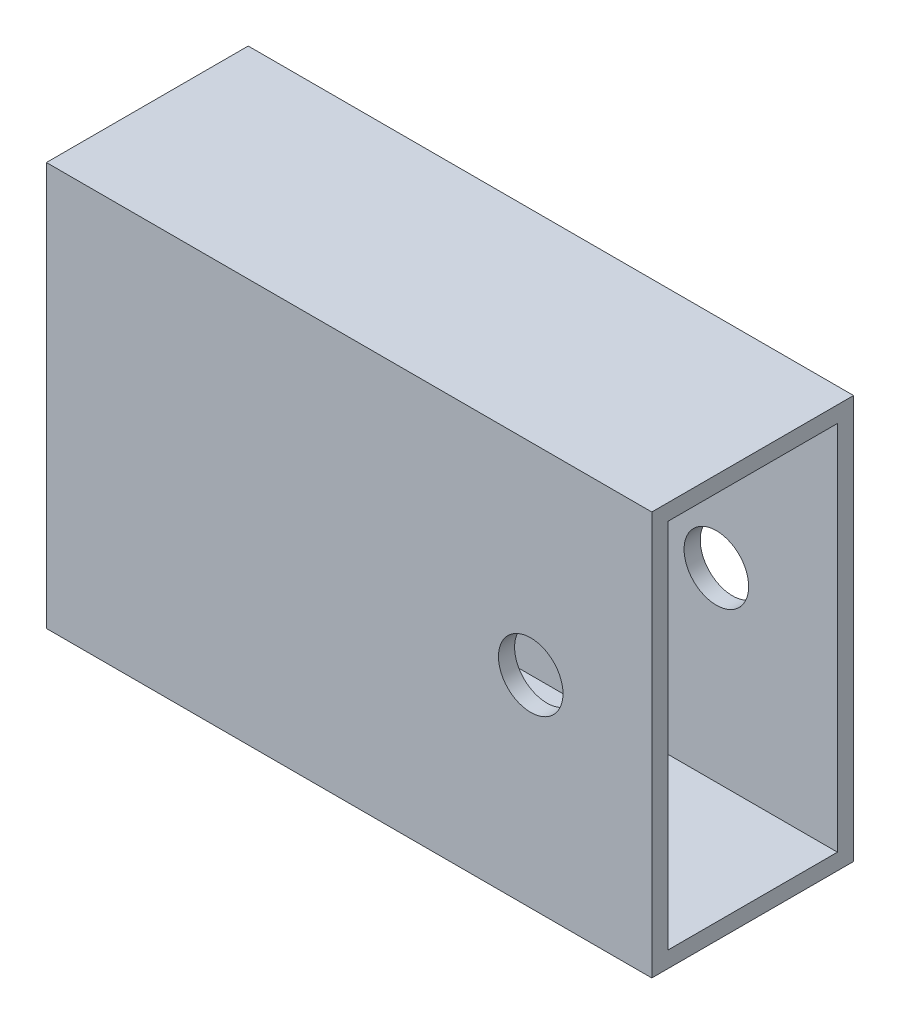
SolidWorks part; units mm, degrees
ref_plane "Front Plane" through (0, 0, 0) normal (0, 0, 1) x (1, 0, 0)
ref_plane "Top Plane" through (0, 0, 0) normal (0, 1, 0) x (1, 0, 0)
ref_plane "Right Plane" through (0, 0, 0) normal (1, 0, 0) x (0, 0, -1)
sketch "Sketch1" plane through (0, 0, 0) normal (1, 0, 0) x (0, 0, -1)
  line L1 (0, 0) -> (25, 0)
  line L2 (0, 0) -> (0, 50)
  line L3 (0, 50) -> (25, 50)
  line L4 (25, 0) -> (25, 50)
  line L5 (2, 2) -> (23, 2)
  line L6 (2, 2) -> (2, 48)
  line L7 (2, 48) -> (23, 48)
  line L8 (23, 2) -> (23, 48)
  dimension "D1" = 25
  dimension "D2" = 50
  dimension "D3" = 2
  dimension "D4" = 2
  dimension "D5" = 2
  dimension "D6" = 2
extrude "Boss-Extrude1" add sketch "Sketch1" along normal blind 75
sketch "Sketch2" plane through (0, 0, 0) normal (0, 0, 1) x (1, 0, 0)
  line L0 (75, 50) -> (75, 0) construction
  line L1 (75, 50) -> (0, 50) construction
  circle A0 centre (60, 25) radius 4
  dimension "D1" = 8
  dimension "D2" = 15
  dimension "D3" = 25
extrude "Cut-Extrude1" cut sketch "Sketch2" against normal through all
